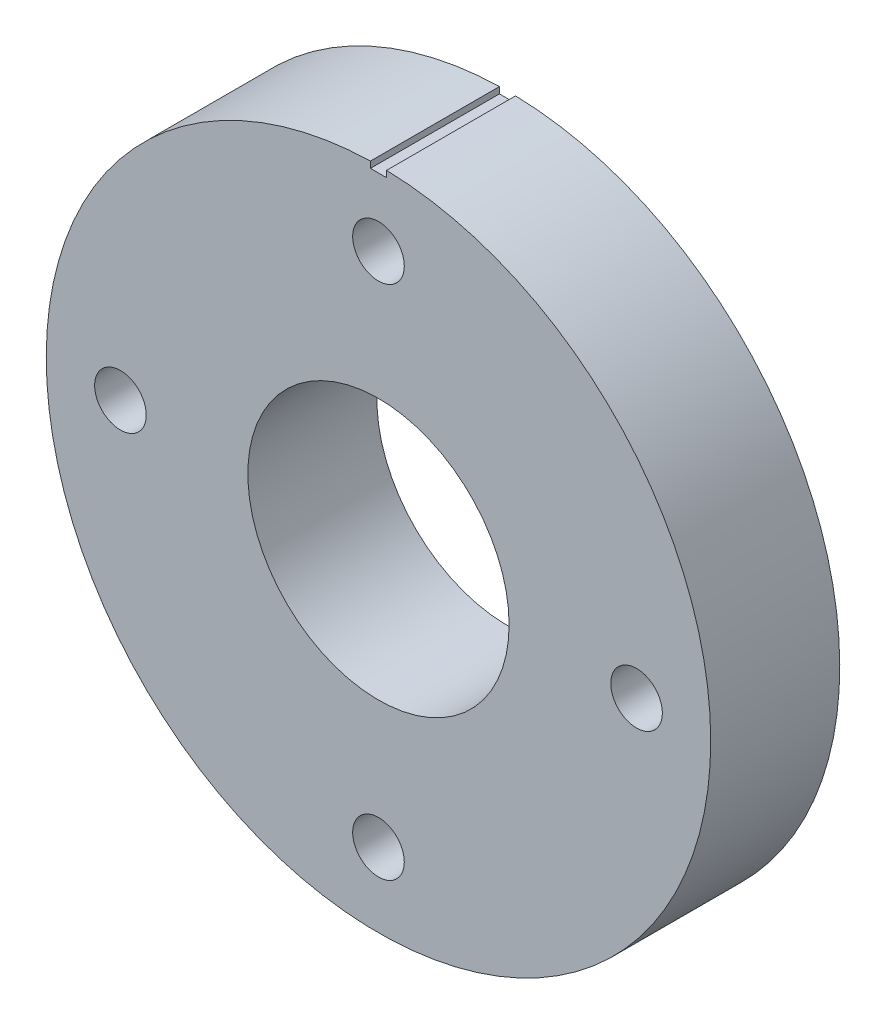
SolidWorks part; units mm, degrees
ref_plane "Front Plane" through (0, 0, 0) normal (0, 0, 1) x (1, 0, 0)
ref_plane "Top Plane" through (0, 0, 0) normal (0, 1, 0) x (1, 0, 0)
ref_plane "Right Plane" through (0, 0, 0) normal (1, 0, 0) x (0, 0, -1)
sketch "Sketch2" plane through (0, 0, 0) normal (0, 0, 1) x (1, 0, 0)
  line L3 (-0.25, -0.9) -> (-0.25, -0.703)
  line L4 (0.25, -0.703) -> (0.25, -0.9)
  line L5 (0.25, -0.9) -> (-0.25, -0.9)
  line L6 (-0.25, -0.9) -> (-0.25, -0.703)
  line L7 (0.25, -0.703) -> (0.25, -0.9)
  line L8 (0.25, -0.9) -> (-0.25, -0.9)
  arc A0 (-8.8, -11) -> (-7.2, -11) centre (-8, -11) ccw construction
  arc A1 (-7.2, -11) -> (-8.8, -11) centre (-8, -11) ccw construction
  arc A2 (-8.8, -11) -> (-7.2, -11) centre (-8, -11) ccw
  arc A3 (-0.25, -0.703) -> (-10.3, -11) centre (0, -11) ccw
  arc A4 (-10.3, -11) -> (10.3, -11) centre (0, -11) ccw
  arc A5 (10.3, -11) -> (0.25, -0.703) centre (0, -11) ccw
  arc A6 (-0.25, -0.703) -> (-10.3, -11) centre (0, -11) ccw
  arc A7 (-10.3, -11) -> (10.3, -11) centre (0, -11) ccw
  arc A8 (10.3, -11) -> (0.25, -0.703) centre (0, -11) ccw
  arc A9 (-7.2, -11) -> (-8.8, -11) centre (-8, -11) ccw
  arc A10 (0.8, -3) -> (-0.8, -3) centre (0, -3) ccw construction
  arc A11 (-0.8, -3) -> (0.8, -3) centre (0, -3) ccw construction
  arc A12 (0.8, -3) -> (-0.8, -3) centre (0, -3) ccw
  arc A13 (-0.8, -3) -> (0.8, -3) centre (0, -3) ccw
  arc A14 (0.8, -19) -> (-0.8, -19) centre (0, -19) ccw construction
  arc A15 (-0.8, -19) -> (0.8, -19) centre (0, -19) ccw construction
  arc A16 (0.8, -19) -> (-0.8, -19) centre (0, -19) ccw
  arc A17 (-0.8, -19) -> (0.8, -19) centre (0, -19) ccw
  arc A18 (8.8, -11) -> (7.2, -11) centre (8, -11) ccw construction
  arc A19 (7.2, -11) -> (8.8, -11) centre (8, -11) ccw construction
  arc A20 (8.8, -11) -> (7.2, -11) centre (8, -11) ccw
  arc A21 (7.2, -11) -> (8.8, -11) centre (8, -11) ccw
  arc A22 (4.05, -11) -> (-4.05, -11) centre (0, -11) ccw construction
  arc A23 (-4.05, -11) -> (4.05, -11) centre (0, -11) ccw construction
  arc A24 (4.05, -11) -> (-4.05, -11) centre (0, -11) ccw
  arc A25 (-4.05, -11) -> (4.05, -11) centre (0, -11) ccw
  dimension "D1" = 0
extrude "Boss-Extrude1" add sketch "Sketch2" along normal blind 4
